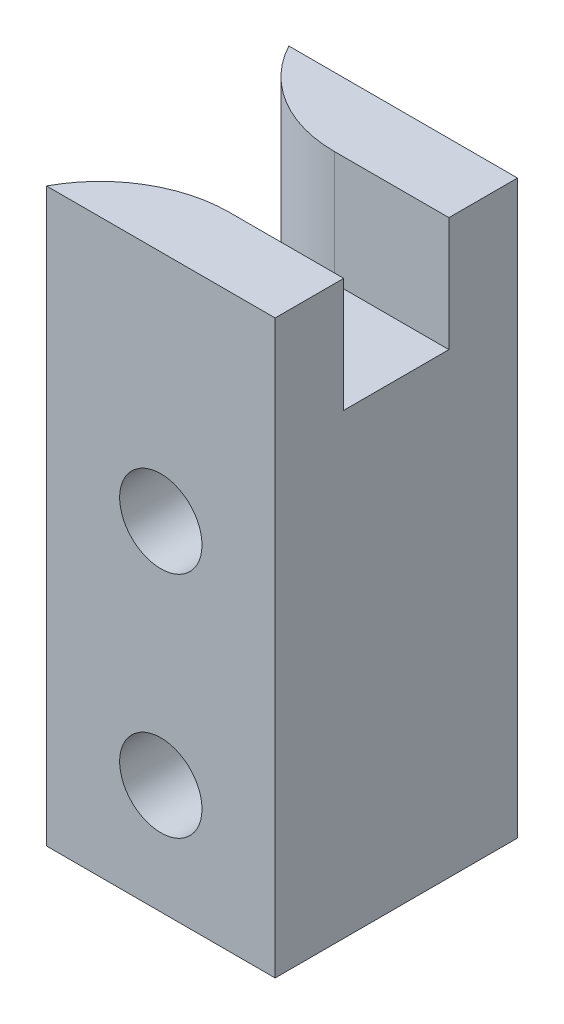
SolidWorks part; units mm, degrees
ref_plane "Front Plane" through (0, 0, 0) normal (0, 0, 1) x (1, 0, 0)
ref_plane "Top Plane" through (0, 0, 0) normal (0, 1, 0) x (1, 0, 0)
ref_plane "Right Plane" through (0, 0, 0) normal (1, 0, 0) x (0, 0, -1)
sketch "Sketch1" plane through (0, 0, 0) normal (0, 1, 0) x (1, 0, 0)
  line L1 (0, 0) -> (10, 0)
  line L2 (0, 0) -> (0, 10.6)
  line L3 (0, 10.6) -> (10, 10.6)
  line L4 (10, 0) -> (10, 10.6)
  dimension "D1" = 10
  dimension "D2" = 10.6
extrude "Boss-Extrude1" add sketch "Sketch1" along normal blind 20
sketch "Sketch3" plane through (0, 0, 0) normal (0, 0, 1) x (1, 0, 0)
  line L0 (0, 20) -> (0, 0) construction
  line L1 (0, 20) -> (10, 20) construction
  line L2 (0, 17.3166) -> (0, 20)
  line L3 (0, 20) -> (5, 20)
  arc A0 (0, 17.3166) -> (5, 20) centre (5, 14) cw
  dimension "D1" = 6
extrude "Cut-Extrude1" cut sketch "Sketch3" against normal through all
sketch "Sketch4" plane through (0, 20, 0) normal (0, 1, 0) x (1, 0, 0)
  line L0 (10, 10.6) -> (0, 10.6)
  line L2 (5, 7.6) -> (10, 7.6)
  line L3 (10, 0) -> (10, 10.6) construction
  line L4 (10, 7.6) -> (10, 10.6)
  line L5 (5, 10.6) -> (5, 0) construction
  line L7 (0, 0) -> (10, 0)
  line L8 (10, 0) -> (10, 3)
  line L9 (10, 3) -> (5, 3)
  arc A0 (0, 10.6) -> (5, 7.6) centre (5, 13.2667) ccw
  arc A1 (5, 3) -> (0, 0) centre (5, -2.6667) ccw
  dimension "D1" = 3
extrude "Boss-Extrude2" add sketch "Sketch4" along normal blind 5 and the other way up to next
sketch "Sketch5" plane through (0, 0, 0) normal (0, 0, 1) x (1, 0, 0)
  line L0 (0, 0) -> (10, 0) construction
  line L1 (5, 4.8) -> (5, 0) construction
  circle A0 centre (5, 14.8) radius 1.8
  circle A1 centre (5, 4.8) radius 1.8
  dimension "D1" = 3.6
  dimension "D2" = 10
  dimension "D3" = 3
extrude "Cut-Extrude2" cut sketch "Sketch5" against normal through all
equation "\"D2@Sketch1\"=1.8+7+1.8"
